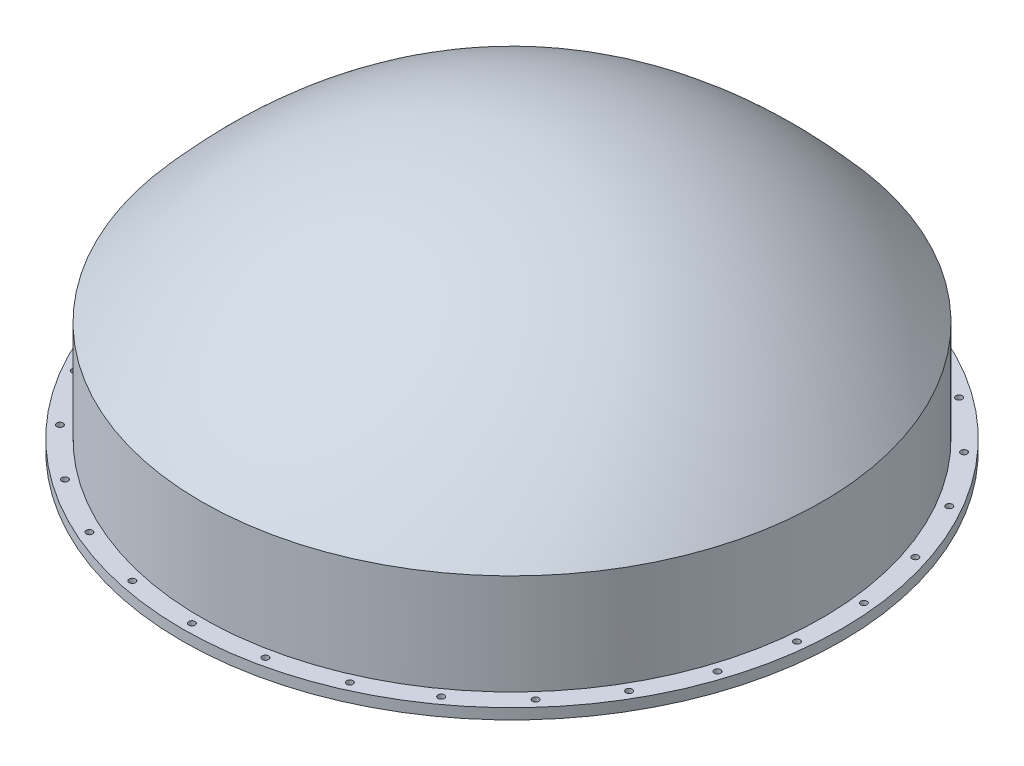
SolidWorks part; units mm, degrees
ref_plane "Front Plane" through (0, 0, 0) normal (0, 0, 1) x (1, 0, 0)
ref_plane "Top Plane" through (0, 0, 0) normal (0, 1, 0) x (1, 0, 0)
ref_plane "Right Plane" through (0, 0, 0) normal (1, 0, 0) x (0, 0, -1)
sketch "Sketch1" plane through (0, 0, 0) normal (1, 0, 0) x (0, 0, -1)
  line L0 (1921.0431, 0) -> (0, 0) construction
  line L1 (0, 0) -> (0, 3491.1264) construction
  line L2 (-2081.13, 0) -> (-2081.13, -744.115)
  line L3 (-931.3985, 1044.41) -> (931.3985, 1044.41) construction
  line L4 (-2130.02, 18.4154) -> (-2130.02, -671.115)
  line L5 (-2081.13, -744.115) -> (-2262.02, -744.115)
  line L6 (-2262.02, -744.115) -> (-2262.02, -671.115)
  line L7 (-2262.02, -671.115) -> (-2130.02, -671.115)
  line L8 (0, 1093.3) -> (0, 1044.41)
  line L9 (-2130.02, 18.4154) -> (-2130.02, -744.115) construction
  spline S0 degree 2 poles (0, 1044.41) (-1164.2481, 1044.41) (-2081.13, 0) knots 0 0 0 1 1 1
  spline S1 degree 1 poles (0, 1093.3) (-2130.02, 18.4154) knots 0 0 1 1 construction
  spline S2 degree 2 poles (0, 1093.3) (-111.9457, 1093.302) (-331.5497, 1074.3322) (-582.6566, 1030.0414) (-861.6415, 945.6732) (-1132.4042, 827.6537) (-1394.7843, 676.1416) (-1616.9632, 514.4202) (-1771.693, 383.3606) (-1878.1563, 284.3819) (-1953.2147, 209.8121) (-2005.296, 155.8083) (-2042.2513, 116.268) (-2068.0055, 88.139) (-2086.3399, 67.8055) (-2099.1459, 53.4589) (-2108.2763, 43.1526) (-2114.6664, 35.9036) (-2119.2082, 30.7311) (-2125.5097, 23.5529) (-2130.02, 18.4154) knots 0 0 0 0.094371 0.188742 0.31457 0.440399 0.566227 0.692055 0.786426 0.84934 0.896526 0.927983 0.951576 0.967304 0.9791 0.986965 0.992863 0.996795 0.999744 1.00171 1.006625 1.006625 1.006625
  dimension "D1" = 2081.13
  dimension "D2" = 1044.41
  dimension "D3" = 744.115
  dimension "D5" = 132
  dimension "D6" = 73
  dimension "D4" = 48.89
revolve "Revolve1" add sketch "Sketch1" angle 360 about L1
sketch "Sketch2" plane through (0, -744.115, 0) normal (0, -1, 0) x (1, 0, 0)
  circle A0 centre (0, 0) radius 2196.0235 construction
  circle A1 centre (0, 2196.0235) radius 22
  circle A2 centre (456.579, 2148.0351) radius 22
  circle A3 centre (893.2032, 2006.1673) radius 22
  circle A4 centre (1290.7902, 1776.6203) radius 22
  circle A5 centre (1631.9635, 1469.4265) radius 22
  circle A6 centre (1901.8121, 1098.0118) radius 22
  circle A7 centre (2088.5425, 678.6086) radius 22
  circle A8 centre (2183.9935, 229.547) radius 22
  circle A9 centre (2183.9935, -229.547) radius 22
  circle A10 centre (2088.5425, -678.6086) radius 22
  circle A11 centre (1901.8121, -1098.0117) radius 22
  circle A12 centre (1631.9635, -1469.4265) radius 22
  circle A13 centre (1290.7902, -1776.6203) radius 22
  circle A14 centre (893.2032, -2006.1673) radius 22
  circle A15 centre (456.579, -2148.0351) radius 22
  circle A16 centre (0, -2196.0235) radius 22
  circle A17 centre (-456.579, -2148.0351) radius 22
  circle A18 centre (-893.2032, -2006.1673) radius 22
  circle A19 centre (-1290.7902, -1776.6203) radius 22
  circle A20 centre (-1631.9635, -1469.4265) radius 22
  circle A21 centre (-1901.8121, -1098.0118) radius 22
  circle A22 centre (-2088.5425, -678.6086) radius 22
  circle A23 centre (-2183.9935, -229.547) radius 22
  circle A24 centre (-2183.9935, 229.547) radius 22
  circle A25 centre (-2088.5425, 678.6086) radius 22
  circle A26 centre (-1901.8121, 1098.0117) radius 22
  circle A27 centre (-1631.9635, 1469.4265) radius 22
  circle A28 centre (-1290.7902, 1776.6203) radius 22
  circle A29 centre (-893.2032, 2006.1673) radius 22
  circle A30 centre (-456.579, 2148.0351) radius 22
  point P66 (0, 0)
  dimension "D1" = 44
  dimension "D2" = 30
extrude "Cut-Extrude1" cut sketch "Sketch2" against normal up to next (73 mm away)
